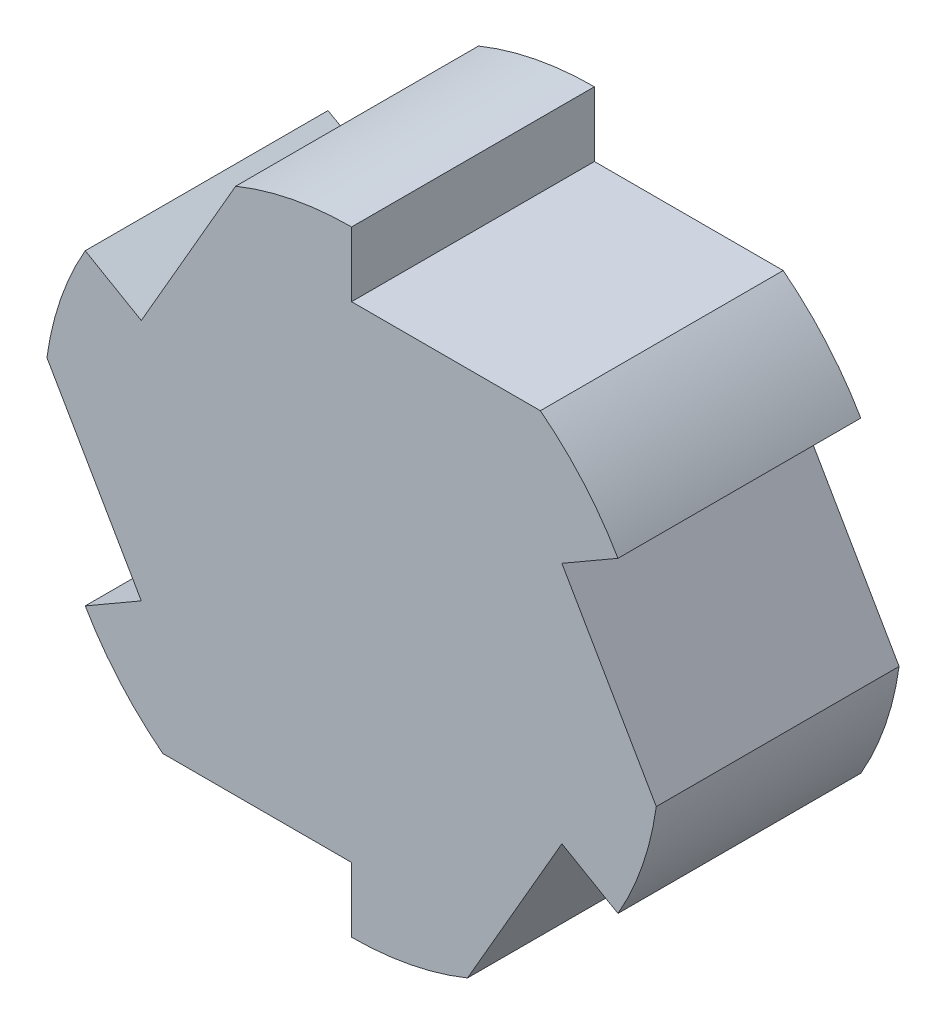
SolidWorks part; units mm, degrees
ref_plane "Front Plane" through (0, 0, 0) normal (0, 0, 1) x (1, 0, 0)
ref_plane "Top Plane" through (0, 0, 0) normal (0, 1, 0) x (1, 0, 0)
ref_plane "Right Plane" through (0, 0, 0) normal (1, 0, 0) x (0, 0, -1)
sketch "Sketch1" plane through (0, 0, 0) normal (0, 0, 1) x (1, 0, 0)
  line L0 (0, 0) -> (0, 30) construction
  line L1 (25.9808, 15) -> (32.909, 19) construction
  line L2 (0, 30) -> (23.3238, 30)
  line L3 (32.909, 19) -> (25.9808, 15)
  line L4 (32.909, -19) -> (25.9808, -15)
  line L5 (25.9808, 15) -> (37.6427, -5.199)
  line L6 (0, -38) -> (0, -30)
  line L7 (25.9808, -15) -> (14.3189, -35.199)
  line L8 (-32.909, -19) -> (-25.9808, -15)
  line L9 (0, -30) -> (-23.3238, -30)
  line L10 (-32.909, 19) -> (-25.9808, 15)
  line L11 (-25.9808, -15) -> (-37.6427, 5.199)
  line L12 (0, 38) -> (0, 30)
  line L13 (-25.9808, 15) -> (-14.3189, 35.199)
  circle A0 centre (0, 0) radius 30
  arc A1 (23.3238, 30) -> (32.909, 19) centre (0, 0) cw
  arc A2 (0, 30) -> (25.9808, 15) centre (0, 0) cw
  circle A3 centre (0, 0) radius 30
  arc A4 (37.6427, -5.199) -> (32.909, -19) centre (0, 0) cw
  circle A5 centre (0, 0) radius 30
  arc A6 (14.3189, -35.199) -> (0, -38) centre (0, 0) cw
  circle A7 centre (0, 0) radius 30
  arc A8 (-23.3238, -30) -> (-32.909, -19) centre (0, 0) cw
  circle A9 centre (0, 0) radius 30
  arc A10 (-37.6427, 5.199) -> (-32.909, 19) centre (0, 0) cw
  circle A11 centre (0, 0) radius 30
  arc A12 (-14.3189, 35.199) -> (0, 38) centre (0, 0) cw
  circle A13 centre (0, 0) radius 38 construction
  circle A14 centre (8.2462, 33.5) radius 3.5
  point P35 (0, 0)
  dimension "D1" = 23.3238
  dimension "D2" = 38
  dimension "D3" = 60
  dimension "D5" = 7
  dimension "D4" = 6
extrude "Boss-Extrude1" add sketch "Sketch1" along normal blind 30 contours A12 L13 A0 L12 | A10 L11 A0 L10 | A8 L9 A0 L8 | A6 L7 A0 L6 | A4 L5 A0 L4 | A1 L2 A0 L3 | A0
